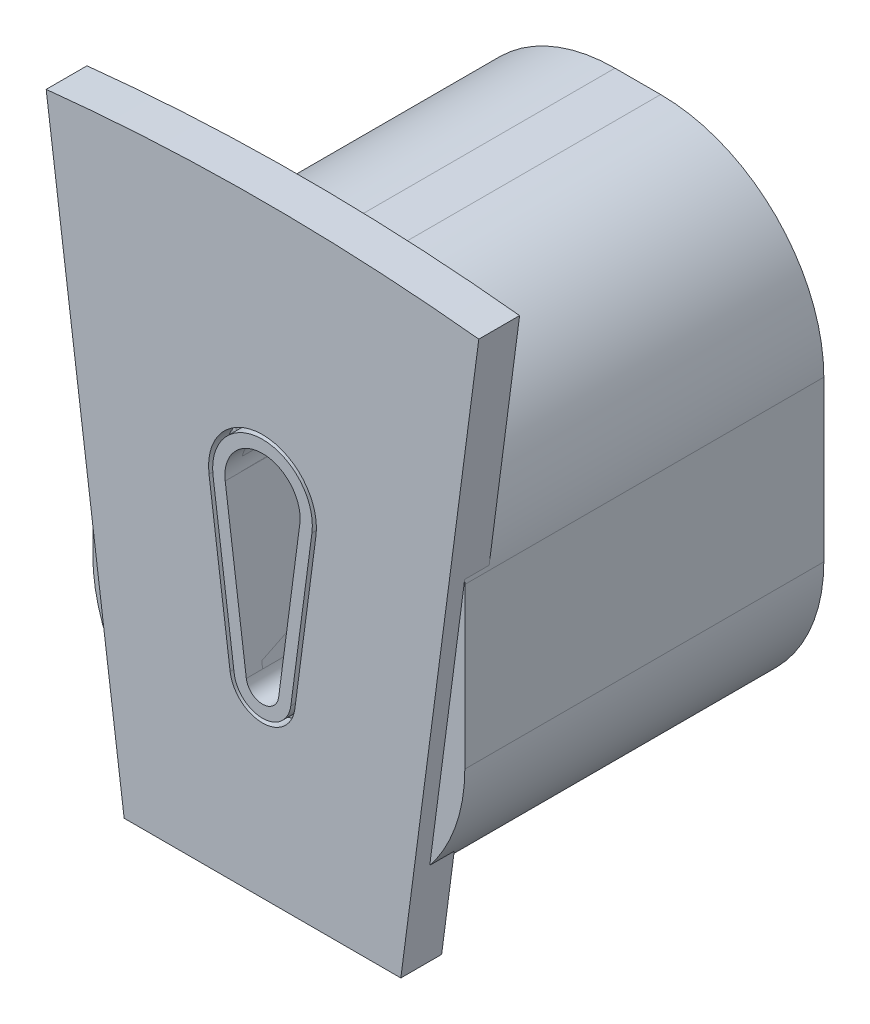
SolidWorks part; units mm, degrees
ref_plane "Front Plane" through (0, 0, 0) normal (0, 0, 1) x (1, 0, 0)
ref_plane "Top Plane" through (0, 0, 0) normal (0, 1, 0) x (1, 0, 0)
ref_plane "Right Plane" through (0, 0, 0) normal (1, 0, 0) x (0, 0, -1)
sketch "Sketch2" plane through (0, 0, 0) normal (0, 0, 1) x (1, 0, 0)
  line L0 (0, 97.2131) -> (0, 91.6338) construction
  line L1 (-8.478, 88) -> (8.478, 88)
  line L6 (-8.478, 88) -> (-7.9903, 84.2951) construction
  line L10 (2.2855, 108.9942) -> (0.9914, 99.1646) construction
  line L11 (-2.2855, 108.9942) -> (-0.9914, 99.1646) construction
  line L12 (0.9914, 99.1646) -> (0, 91.6338) construction
  line L13 (8.478, 88) -> (7.9903, 84.2951) construction
  line L14 (0, 91.6338) -> (0, 98.2951) construction
  line L15 (0, 98.2951) -> (0, 145) construction
  line L16 (-0.9914, 99.1646) -> (0.0011, 91.6255) construction
  line L17 (-3.277, 108.8637) -> (-1.9829, 99.034)
  line L23 (-13.2564, 124.2951) -> (-8.478, 88)
  line L24 (13.2564, 124.2951) -> (8.478, 88)
  line L25 (3.277, 108.8637) -> (1.9829, 99.034)
  line L44 (-7.9903, 84.2951) -> (7.9903, 84.2951) construction
  arc A0 (50.4049, 135.9571) -> (-50.4049, 135.9571) centre (0, 0) ccw construction
  arc A4 (2.2855, 108.9942) -> (-2.2855, 108.9942) centre (0, 109.2951) ccw construction
  arc A6 (-0.9914, 99.1646) -> (0.9914, 99.1646) centre (0, 99.2951) ccw construction
  arc A7 (-13.2564, 124.2951) -> (13.2564, 124.2951) centre (0, 0) cw
  arc A12 (3.277, 108.8637) -> (-3.277, 108.8637) centre (0, 109.2951) ccw
  arc A14 (-1.9829, 99.034) -> (1.9829, 99.034) centre (0, 99.2951) ccw
  arc A15 (-0.6288, 112.933) -> (0, 112.8692) centre (-0.6156, 109.933) cw construction
  arc A16 (0, 112.8692) -> (0.6288, 112.933) centre (0.6156, 109.933) cw construction
  dimension "D3" = 15
  dimension "D4" = 1
  dimension "D5" = 10
  dimension "D6" = 40
  dimension "D1" = 15
  dimension "D9" = 88
  dimension "D2" = 125
  dimension "D7" = 1
extrude "Boss-Extrude1" add sketch "Sketch2" along normal blind 2.5 contours L24 L1 L23 A7 | L17 A14 L25 A12
sketch "Sketch4" plane through (0, 0, 2.5) normal (0, 0, 1) x (1, 0, 0)
  line L0 (0.9914, 99.1646) -> (2.2855, 108.9942)
  line L1 (-2.2855, 108.9942) -> (-0.9914, 99.1646)
  line L4 (-3.0291, 108.8963) -> (-1.735, 99.0667)
  line L5 (1.735, 99.0667) -> (3.0291, 108.8963)
  line L6 (-3.0291, 108.8963) -> (-1.735, 99.0667)
  line L7 (1.735, 99.0667) -> (3.0291, 108.8963)
  arc A0 (-0.9914, 99.1646) -> (0.9914, 99.1646) centre (0, 99.2951) ccw
  arc A1 (2.2855, 108.9942) -> (-2.2855, 108.9942) centre (0, 109.2951) ccw
  arc A4 (-1.735, 99.0667) -> (1.735, 99.0667) centre (0, 99.2951) ccw
  arc A5 (3.0291, 108.8963) -> (-3.0291, 108.8963) centre (0, 109.2951) ccw
  arc A6 (-1.735, 99.0667) -> (1.735, 99.0667) centre (0, 99.2951) ccw
  arc A7 (3.0291, 108.8963) -> (-3.0291, 108.8963) centre (0, 109.2951) ccw
  dimension "D1" = 0.25
  dimension "D2" = 0.75
extrude "Boss-Extrude2" add sketch "Sketch4" against normal blind 1 separate body
sketch "Sketch6" plane through (0, 0, 1.5) normal (0, 0, -1) x (-1, 0, 0)
  line L2 (2.2855, 108.9942) -> (0.9914, 99.1646) construction
  line L3 (-0.9914, 99.1646) -> (-2.2855, 108.9942) construction
  line L4 (2.7265, 98.9361) -> (4.0206, 108.7658)
  line L5 (-4.0206, 108.7658) -> (-2.7265, 98.9361)
  line L6 (2.7265, 98.9361) -> (4.0206, 108.7658)
  line L7 (-4.0206, 108.7658) -> (-2.7265, 98.9361)
  line L8 (2.2855, 108.9942) -> (0.9914, 99.1646)
  line L9 (-0.9914, 99.1646) -> (-2.2855, 108.9942)
  arc A2 (-0.9914, 99.1646) -> (0.9914, 99.1646) centre (0, 99.2951) ccw construction
  arc A3 (2.2855, 108.9942) -> (-2.2855, 108.9942) centre (0, 109.2951) ccw construction
  arc A4 (-2.7265, 98.9361) -> (2.7265, 98.9361) centre (0, 99.2951) ccw
  arc A5 (4.0206, 108.7658) -> (-4.0206, 108.7658) centre (0, 109.2951) ccw
  arc A6 (-2.7265, 98.9361) -> (2.7265, 98.9361) centre (0, 99.2951) ccw
  arc A7 (4.0206, 108.7658) -> (-4.0206, 108.7658) centre (0, 109.2951) ccw
  arc A8 (-0.9914, 99.1646) -> (0.9914, 99.1646) centre (0, 99.2951) ccw
  arc A9 (2.2855, 108.9942) -> (-2.2855, 108.9942) centre (0, 109.2951) ccw
  dimension "D1" = 1
extrude "Boss-Extrude3" add sketch "Sketch6" along normal blind 22
sketch "Sketch7" plane through (0, 0, 2.5) normal (0, 0, 1) x (1, 0, 0)
  line L0 (0.9914, 99.1646) -> (2.2855, 108.9942) construction
  line L1 (-2.2855, 108.9942) -> (-0.9914, 99.1646) construction
  line L2 (1.735, 99.0667) -> (3.0291, 108.8963)
  line L3 (-3.0291, 108.8963) -> (-1.735, 99.0667)
  line L4 (1.735, 99.0667) -> (3.0291, 108.8963)
  line L5 (-3.0291, 108.8963) -> (-1.735, 99.0667)
  line L6 (0.9914, 99.1646) -> (2.2855, 108.9942)
  line L7 (-2.2855, 108.9942) -> (-0.9914, 99.1646)
  arc A0 (-0.9914, 99.1646) -> (0.9914, 99.1646) centre (0, 99.2951) ccw construction
  arc A1 (2.2855, 108.9942) -> (-2.2855, 108.9942) centre (0, 109.2951) ccw construction
  arc A2 (-1.735, 99.0667) -> (1.735, 99.0667) centre (0, 99.2951) ccw
  arc A3 (3.0291, 108.8963) -> (-3.0291, 108.8963) centre (0, 109.2951) ccw
  arc A4 (-1.735, 99.0667) -> (1.735, 99.0667) centre (0, 99.2951) ccw
  arc A5 (3.0291, 108.8963) -> (-3.0291, 108.8963) centre (0, 109.2951) ccw
  arc A6 (-0.9914, 99.1646) -> (0.9914, 99.1646) centre (0, 99.2951) ccw
  arc A7 (2.2855, 108.9942) -> (-2.2855, 108.9942) centre (0, 109.2951) ccw
  dimension "D1" = 0
extrude "Boss-Extrude4" add sketch "Sketch7" against normal blind 1 from surface at -23 starting at face at (0, 104.3993, -20.5)
sketch "Sketch9" plane through (0, 0, 1.5) normal (0, 0, 1) x (1, 0, 0)
  line L0 (0, 111.6003) -> (0, 98.2951) construction
  line L1 (-1.4, 119.8477) -> (1.4, 119.8477)
  line L2 (-11.4, 109.8477) -> (-11.4, 100.0477)
  line L3 (-1.4, 90.0477) -> (1.4, 90.0477)
  line L4 (11.4, 109.8477) -> (11.4, 100.0477)
  line L5 (-11.4, 119.8477) -> (11.4, 90.0477) construction
  line L6 (-11.4, 90.0477) -> (11.4, 119.8477) construction
  line L7 (0.9914, 99.1646) -> (2.2855, 108.9942) construction
  line L8 (-2.2855, 108.9942) -> (-0.9914, 99.1646) construction
  line L9 (0.9914, 99.1646) -> (2.2855, 108.9942)
  line L10 (-2.2855, 108.9942) -> (-0.9914, 99.1646)
  arc A0 (2.2855, 108.9942) -> (-2.2855, 108.9942) centre (0, 109.2951) ccw construction
  arc A1 (-0.9914, 99.1646) -> (0.9914, 99.1646) centre (0, 99.2951) ccw construction
  arc A2 (1.4, 119.8477) -> (11.4, 109.8477) centre (1.4, 109.8477) cw
  arc A3 (11.4, 100.0477) -> (1.4, 90.0477) centre (1.4, 100.0477) cw
  arc A4 (-11.4, 100.0477) -> (-1.4, 90.0477) centre (-1.4, 100.0477) ccw
  arc A5 (-11.4, 109.8477) -> (-1.4, 119.8477) centre (-1.4, 109.8477) cw
  arc A6 (-0.9914, 99.1646) -> (0.9914, 99.1646) centre (0, 99.2951) ccw
  arc A7 (2.2855, 108.9942) -> (-2.2855, 108.9942) centre (0, 109.2951) ccw
  point P0 (0, 104.9477)
  dimension "D3" = 10
  dimension "D1" = 29.8
  dimension "D2" = 22.8
extrude "Boss-Extrude5" add sketch "Sketch9" against normal up to surface (22 mm away) separate body up to face at (0, 104.3993, -20.5)
